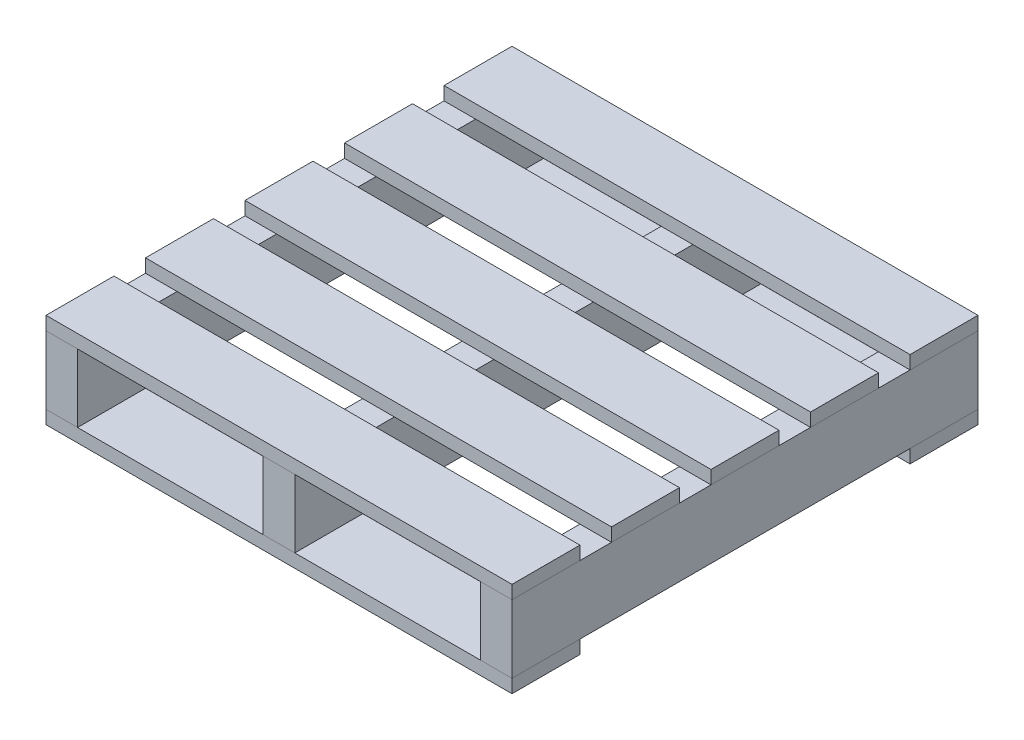
SolidWorks part; units mm, degrees
ref_plane "Front Plane" through (0, 0, 0) normal (0, 0, 1) x (1, 0, 0)
ref_plane "Top Plane" through (0, 0, 0) normal (0, 1, 0) x (1, 0, 0)
ref_plane "Right Plane" through (0, 0, 0) normal (1, 0, 0) x (0, 0, -1)
sketch "Sketch1" plane through (0, 0, 0) normal (0, 0, 1) x (1, 0, 0)
  line L0 (-304.8, 0) -> (304.8, 0) construction
  line L5 (-304.8, 61.976) -> (-304.8, -61.976) construction
  line L6 (304.8, 61.976) -> (304.8, -61.976) construction
  line L11 (-304.8, -61.976) -> (304.8, -61.976) construction
  line L12 (-304.8, 61.976) -> (304.8, 61.976) construction
  line L13 (-263.525, 61.976) -> (-263.525, -61.976) construction
  line L14 (263.525, 61.976) -> (263.525, -61.976) construction
  line L15 (-20.701, 61.976) -> (-20.701, -61.976) construction
  line L16 (20.701, -61.976) -> (20.701, 61.976) construction
  line L17 (0, 61.976) -> (0, -61.976) construction
  line L18 (-304.8, 0) -> (-263.525, 0)
  line L19 (-20.701, 0) -> (0, 0)
  line L20 (0, 0) -> (20.701, 0)
  line L21 (263.525, 0) -> (304.8, 0)
  line L22 (-304.8, 44.5008) -> (304.8, 44.5008) construction
  line L23 (-304.8, -44.5008) -> (304.8, -44.5008) construction
  point P3 (0, 0)
  point P6 (-304.8, 0)
  point P9 (304.8, 0)
  point P23 (0, 0)
  dimension "Width" = 609.6
  dimension "Height" = 123.952
  dimension "Maximum Fork Width" = 242.824
  dimension "D2" = 242.824
  dimension "Maximum Fork Height" = 89.0016
  dimension "D1" = 41.275
  dimension "D3" = 17.4752
sketch "Sketch2" plane through (0, 0, 0) normal (1, 0, 0) x (0, 0, -1)
  line L0 (304.8, 0) -> (-304.8, 0) construction
  point P4 (0, 0)
  dimension "Depth" = 609.6
sketch "Sketch3" plane through (0, 0, 0) normal (0, 0, 1) x (1, 0, 0)
  line L0 (-263.525, 61.976) -> (-263.525, -61.976) construction
  line L1 (-304.8, 44.5008) -> (-263.525, 44.5008)
  line L2 (-304.8, 44.5008) -> (-304.8, -44.5008)
  line L3 (-304.8, -44.5008) -> (-263.525, -44.5008)
  line L4 (-263.525, 44.5008) -> (-263.525, -44.5008)
  line L5 (-304.8, -44.5008) -> (304.8, -44.5008) construction
  line L6 (-20.701, 61.976) -> (-20.701, -61.976) construction
  line L7 (-20.701, 44.5008) -> (20.701, 44.5008)
  line L8 (-20.701, 44.5008) -> (-20.701, -44.5008)
  line L9 (-20.701, -44.5008) -> (20.701, -44.5008)
  line L10 (20.701, 44.5008) -> (20.701, -44.5008)
  line L11 (-304.8, 44.5008) -> (304.8, 44.5008) construction
  line L12 (20.701, -61.976) -> (20.701, 61.976) construction
  line L13 (263.525, 61.976) -> (263.525, -61.976) construction
  line L14 (263.525, 44.5008) -> (304.8, 44.5008)
  line L15 (263.525, 44.5008) -> (263.525, -44.5008)
  line L16 (263.525, -44.5008) -> (304.8, -44.5008)
  line L17 (304.8, 44.5008) -> (304.8, -44.5008)
extrude "Boss-Extrude1" add sketch "Sketch3" along normal up to vertex (304.8 mm away) and the other way up to vertex (304.8 mm away) up to point (0, 0, 304.8) other way up to point (0, 0, -304.8)
sketch "Sketch4" plane through (0, 44.5008, 0) normal (0, 1, 0) x (1, 0, 0)
  line L0 (304.8, -304.8) -> (304.8, 304.8) construction
  line L1 (-304.8, -304.8) -> (304.8, -304.8)
  line L2 (-304.8, -304.8) -> (-304.8, -215.9)
  line L3 (-304.8, -215.9) -> (304.8, -215.9)
  line L4 (304.8, -304.8) -> (304.8, -215.9)
  line L5 (-304.8, -174.625) -> (304.8, -174.625)
  line L6 (-304.8, -174.625) -> (-304.8, -85.725)
  line L7 (-304.8, -85.725) -> (304.8, -85.725)
  line L8 (304.8, -174.625) -> (304.8, -85.725)
  line L9 (-304.8, -44.45) -> (304.8, -44.45)
  line L10 (-304.8, -44.45) -> (-304.8, 44.45)
  line L11 (-304.8, 44.45) -> (304.8, 44.45)
  line L12 (304.8, -44.45) -> (304.8, 44.45)
  line L13 (-304.8, 85.725) -> (304.8, 85.725)
  line L14 (-304.8, 85.725) -> (-304.8, 174.625)
  line L15 (-304.8, 174.625) -> (304.8, 174.625)
  line L16 (304.8, 85.725) -> (304.8, 174.625)
  line L17 (-304.8, 215.9) -> (304.8, 215.9)
  line L18 (-304.8, 215.9) -> (-304.8, 304.8)
  line L19 (-304.8, 304.8) -> (304.8, 304.8)
  line L20 (304.8, 215.9) -> (304.8, 304.8)
  line L21 (-304.8, -304.8) -> (-304.8, 304.8) construction
  line L22 (-263.525, 304.8) -> (-304.8, 304.8) construction
  dimension "D1" = 88.9
  dimension "D2" = 5
extrude "Boss-Extrude2" add sketch "Sketch4" along normal up to vertex (17.4752 mm away) separate body up to point (-304.8, 61.976, 0)
sketch "Sketch5" plane through (0, -44.5008, 0) normal (0, -1, 0) x (1, 0, 0)
  line L1 (-304.8, 304.8) -> (304.8, 304.8)
  line L2 (-304.8, 304.8) -> (-304.8, 215.9)
  line L3 (-304.8, 215.9) -> (304.8, 215.9)
  line L4 (304.8, 304.8) -> (304.8, 215.9)
  line L5 (-304.8, -304.8) -> (304.8, -304.8)
  line L6 (-304.8, -304.8) -> (-304.8, -215.9)
  line L7 (-304.8, -215.9) -> (304.8, -215.9)
  line L8 (304.8, -304.8) -> (304.8, -215.9)
extrude "Boss-Extrude3" add sketch "Sketch5" along normal up to vertex (17.4752 mm away) separate body up to point (-304.8, -61.976, 0)
equation "\"D2@Sketch1\" = \"Maximum Fork Width@Sketch1\""
